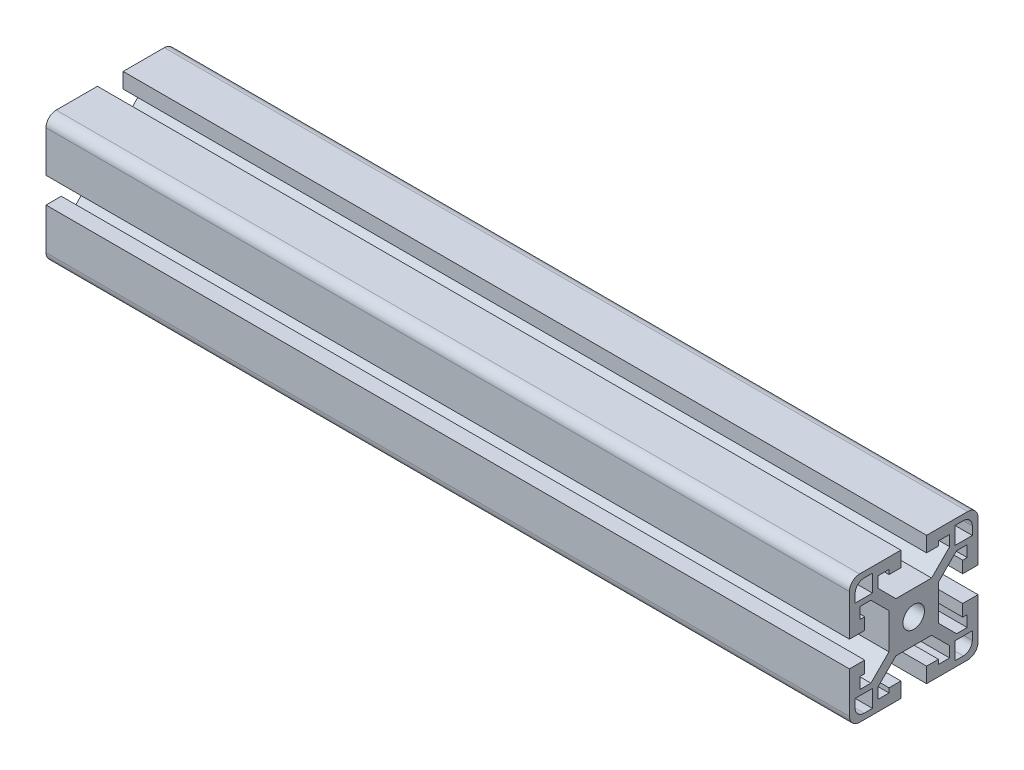
SolidWorks part; units mm, degrees
material "6063-T6"
ref_plane "Front Plane" through (0, 0, 0) normal (0, 0, 1) x (1, 0, 0)
ref_plane "Top Plane" through (0, 0, 0) normal (0, 1, 0) x (1, 0, 0)
ref_plane "Right Plane" through (0, 0, 0) normal (1, 0, 0) x (0, 0, -1)
sketch "Sketch1" plane through (0, 0, 0) normal (0, 1, 0) x (1, 0, 0)
  line L0 (-125, 0) -> (125, 0)
  dimension "D1" = 250
other "40 series TS40-40LM-650033(1)"
ref_plane "Plane1" through (-125, 0, 0) normal (1, 0, 0) x (0, 0, -1)
sketch "Sketch2" plane through (-125, 0, 0) normal (1, 0, 0) x (0, 0, -1)
  line L2 (-7.7064, 0) -> (-7.7064, 5.5511)
  line L3 (-7.7064, 5.5511) -> (-13.3313, 11.176)
  line L4 (-16.6472, 11.176) -> (-16.6472, 7.6835)
  line L5 (5.5511, 7.7064) -> (11.176, 13.3313)
  line L6 (-20, 4.0005) -> (-20, 16.825)
  line L7 (0, 7.7064) -> (-5.5511, 7.7064)
  line L8 (-5.5511, 7.7064) -> (-11.176, 13.3313)
  line L9 (-11.176, 16.6472) -> (-7.6835, 16.6472)
  line L10 (4.0005, 20) -> (16.825, 20)
  line L11 (-4.0005, 20) -> (-16.825, 20)
  line L12 (20, 4.0005) -> (20, 16.825)
  line L13 (7.7064, 5.5511) -> (13.3313, 11.176)
  line L14 (18.222, 12.8372) -> (18.222, 15.428)
  line L15 (12.8372, 18.222) -> (15.428, 18.222)
  line L16 (7.7064, 0) -> (7.7064, 5.5511)
  line L17 (7.7064, 0) -> (7.7064, -5.5511)
  line L18 (7.6835, 16.6472) -> (7.6835, 15.2502)
  line L19 (4.0005, 15.2502) -> (7.6835, 15.2502)
  line L20 (11.176, -13.3313) -> (11.176, -16.6472)
  line L21 (13.3313, -11.176) -> (16.6472, -11.176)
  line L22 (20, -4.0005) -> (20, -16.825)
  line L23 (-4.0005, -20) -> (-16.825, -20)
  line L24 (4.0005, -20) -> (16.825, -20)
  line L25 (12.8372, -12.8372) -> (18.222, -12.8372)
  line L26 (-18.222, -12.8372) -> (-18.222, -15.428)
  line L27 (-12.8372, -18.222) -> (-15.428, -18.222)
  line L28 (-20, -4.0005) -> (-20, -16.825)
  line L29 (-12.8372, -12.8372) -> (-12.8372, -18.222)
  line L30 (-12.8372, -12.8372) -> (-18.222, -12.8372)
  line L31 (12.8372, -12.8372) -> (12.8372, -18.222)
  line L32 (-7.7064, 0) -> (-7.7064, -5.5511)
  line L33 (0, 7.7064) -> (5.5511, 7.7064)
  line L34 (-4.0005, 20) -> (-4.0005, 15.2502)
  line L35 (4.0005, 20) -> (4.0005, 15.2502)
  line L36 (-15.2502, 4.0005) -> (-20, 4.0005)
  line L37 (15.2502, 4.0005) -> (15.2502, 7.6835)
  line L38 (16.6472, 7.6835) -> (15.2502, 7.6835)
  line L39 (15.2502, 4.0005) -> (20, 4.0005)
  line L40 (11.176, 16.6472) -> (7.6835, 16.6472)
  line L41 (16.6472, 11.176) -> (16.6472, 7.6835)
  line L42 (-11.176, 13.3313) -> (-11.176, 16.6472)
  line L43 (-13.3313, 11.176) -> (-16.6472, 11.176)
  line L44 (12.8372, 12.8372) -> (12.8372, 18.222)
  line L45 (-12.8372, 12.8372) -> (-18.222, 12.8372)
  line L46 (-12.8372, 12.8372) -> (-12.8372, 18.222)
  line L47 (-12.8372, 18.222) -> (-15.428, 18.222)
  line L48 (-18.222, 12.8372) -> (-18.222, 15.428)
  line L49 (12.8372, 12.8372) -> (18.222, 12.8372)
  line L50 (13.3313, 11.176) -> (16.6472, 11.176)
  line L51 (11.176, 13.3313) -> (11.176, 16.6472)
  line L52 (-11.176, -16.6472) -> (-7.6835, -16.6472)
  line L53 (11.176, -16.6472) -> (7.6835, -16.6472)
  line L54 (-13.3313, -11.176) -> (-16.6472, -11.176)
  line L55 (-11.176, -13.3313) -> (-11.176, -16.6472)
  line L56 (0, -7.7064) -> (5.5511, -7.7064)
  line L57 (12.8372, -18.222) -> (15.428, -18.222)
  line L58 (18.222, -12.8372) -> (18.222, -15.428)
  line L59 (7.7064, -5.5511) -> (13.3313, -11.176)
  line L60 (16.6472, -11.176) -> (16.6472, -7.6835)
  line L61 (-5.5511, -7.7064) -> (-11.176, -13.3313)
  line L62 (0, -7.7064) -> (-5.5511, -7.7064)
  line L63 (5.5511, -7.7064) -> (11.176, -13.3313)
  line L64 (15.2502, -4.0005) -> (20, -4.0005)
  line L65 (-7.7064, -5.5511) -> (-13.3313, -11.176)
  line L66 (16.6472, -7.6835) -> (15.2502, -7.6835)
  line L67 (15.2502, -4.0005) -> (15.2502, -7.6835)
  line L68 (4.0005, -20) -> (4.0005, -15.2502)
  line L69 (-4.0005, 15.2502) -> (-7.6835, 15.2502)
  line L70 (-7.6835, 16.6472) -> (-7.6835, 15.2502)
  line L71 (4.0005, -15.2502) -> (7.6835, -15.2502)
  line L72 (7.6835, -16.6472) -> (7.6835, -15.2502)
  line L73 (-16.6472, 7.6835) -> (-15.2502, 7.6835)
  line L74 (-15.2502, 4.0005) -> (-15.2502, 7.6835)
  line L75 (-7.6835, -16.6472) -> (-7.6835, -15.2502)
  line L76 (-4.0005, -15.2502) -> (-7.6835, -15.2502)
  line L77 (-4.0005, -20) -> (-4.0005, -15.2502)
  line L78 (-15.2502, -4.0005) -> (-15.2502, -7.6835)
  line L79 (-16.6472, -7.6835) -> (-15.2502, -7.6835)
  line L80 (-15.2502, -4.0005) -> (-20, -4.0005)
  line L81 (-16.6472, -11.176) -> (-16.6472, -7.6835)
  arc A0 (-16.825, 20) -> (-20, 16.825) centre (-16.825, 16.825) ccw
  arc A1 (-15.428, 18.222) -> (-18.222, 15.428) centre (-15.428, 15.428) ccw
  arc A2 (15.428, 18.222) -> (18.222, 15.428) centre (15.428, 15.428) cw
  arc A3 (-15.428, -18.222) -> (-18.222, -15.428) centre (-15.428, -15.428) cw
  arc A4 (15.428, -18.222) -> (18.222, -15.428) centre (15.428, -15.428) ccw
  arc A5 (16.825, 20) -> (20, 16.825) centre (16.825, 16.825) cw
  arc A6 (16.825, -20) -> (20, -16.825) centre (16.825, -16.825) ccw
  arc A7 (-16.825, -20) -> (-20, -16.825) centre (-16.825, -16.825) cw
  circle A8 centre (0, 0) radius 3.35
  point P1 (-20, 20)
  point P2 (0, 20)
  point P100 (20, 20)
  point P101 (20, 0)
  point P102 (20, -20)
  point P103 (0, -20)
  point P104 (-20, -20)
  point P105 (-20, 0)
  point P106 (0, 0)
  dimension "D1" = 6.7
